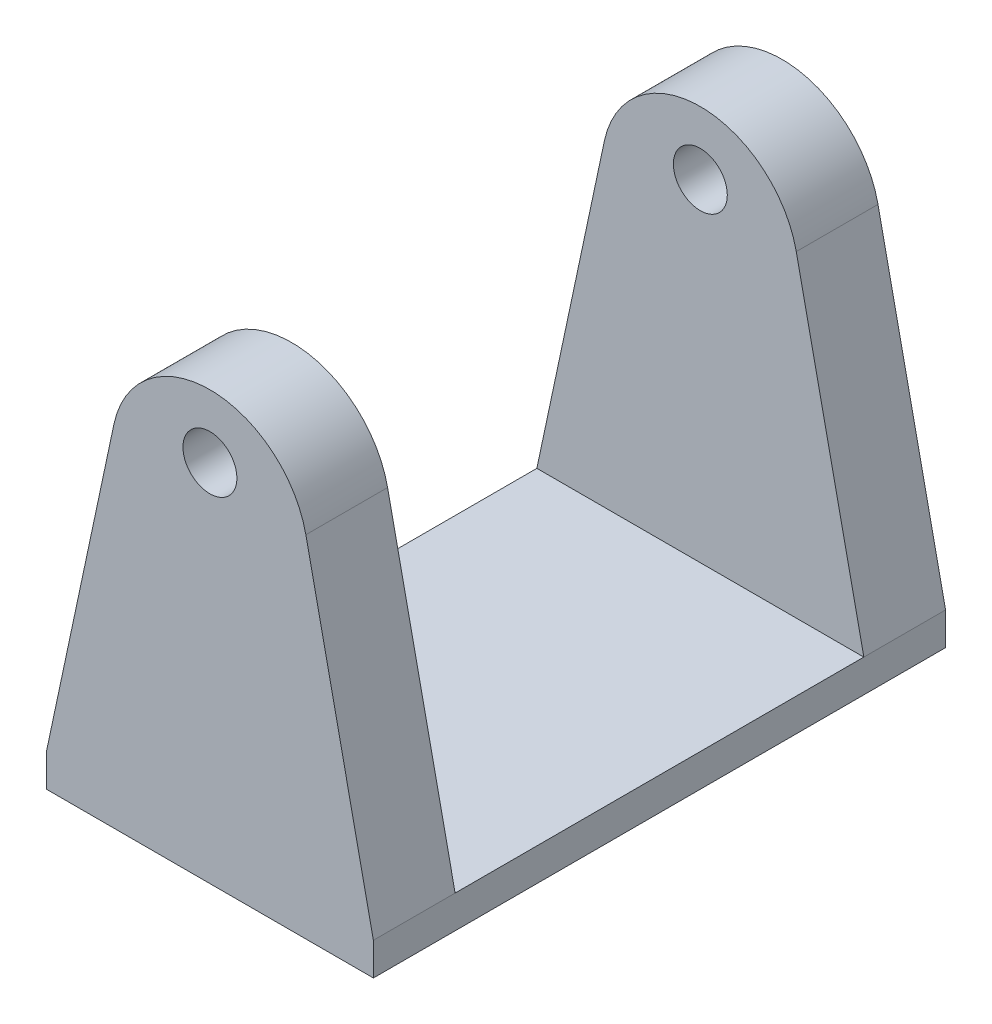
SolidWorks part; units mm, degrees
ref_plane "Front Plane" through (0, 0, 0) normal (0, 0, 1) x (1, 0, 0)
ref_plane "Top Plane" through (0, 0, 0) normal (0, 1, 0) x (1, 0, 0)
ref_plane "Right Plane" through (0, 0, 0) normal (1, 0, 0) x (0, 0, -1)
sketch "Sketch2" plane through (0, 0, 0) normal (0, 1, 0) x (1, 0, 0)
  line L1 (0, 0) -> (20, 0)
  line L2 (0, 0) -> (0, 35)
  line L3 (0, 35) -> (20, 35)
  line L4 (20, 0) -> (20, 35)
extrude "Boss-Extrude2" add sketch "Sketch2" along normal blind 2
sketch3d "3DSketch3"
  line L0 (10, 2, 0) -> (10, 49, 0)
  line L1 (0, 2, 0) -> (20, 2, 0) construction
  line L2 (10, 49, 0) -> (0, 2, 0)
  line L3 (0, 2, 0) -> (20, 2, 0)
  line L4 (20, 2, 0) -> (10, 49, 0)
  point P8 (0, 0, 0)
  point P9 (10, 25.828, 0)
  point P10 (10, 53.1292, 0)
  point P11 (10, 50.8187, 0)
extrude "Boss-Extrude5" add sketch "3DSketch3" along direction (0, 0, 1) on the side against the normal blind 5 contours L2 L3 L4
sketch3d "3DSketch4"
  line L0 (10, 2, -35) -> (10, 49, -35)
  line L1 (20, 2, -35) -> (0, 2, -35) construction
  line L2 (10, 49, -35) -> (0, 2, -35)
  line L3 (0, 2, -35) -> (20, 2, -35)
  line L4 (20, 2, -35) -> (10, 49, -35)
  point P8 (10, 45.7333, -35)
  point P9 (10, 50.8103, -35)
  point P10 (10, 48.7995, -35)
  point P11 (10, 37.9936, -35)
  point P12 (10, 56.0697, -35)
  point P13 (10, 51.4178, -35)
  point P14 (10, 45.4786, -35)
extrude "Boss-Extrude6" add sketch "3DSketch4" along direction (0, 0, 1) on the side of the normal blind 5 contours L2 L3 L4
fillet "Fillet1" radius 6 2 edges
sketch3d "3DSketch5"
  line L0 (10, 2, -5) -> (10, 22.3, -5)
  line L1 (0, 2, -5) -> (20, 2, -5) construction
  line L2 (10, 2, -30) -> (10, 22.3, -30)
  line L3 (0, 2, -30) -> (20, 2, -30) construction
  point P8 (0, 0, 0)
  point P9 (10, 15.4405, -5)
  point P10 (10, 13.0209, -5)
  point P11 (10, 13.0209, -5)
  point P12 (10, 22.5355, -5)
  point P13 (10, 12.0863, -30)
  point P14 (10, 20.5807, -30)
hole_wizard "Preforo da maschiare M4-1" positions "Sketch4" profile "Sketch5" hole size "M4" standard "GB"
sketch "Sketch4" plane through (0, 0, -30) normal (0, 0, 1) x (1, 0, 0)
  point P0 (10, 22.3)
sketch "Sketch5" plane through (10, 22.3, -30) normal (1, 0, 0) x (0, -1, 0)
  line L0 (0, 0) -> (0, 5.0001)
  line L1 (0, 5.0001) -> (1.65, 5.0001)
  line L2 (1.65, 5.0001) -> (1.65, 0)
  line L5 (1.65, 0) -> (0, 0)
  line L11 (0, -6.35) -> (0, 107.95) construction
  dimension "Thru Hole Dia." = 3.3
  dimension "Thru Hole Depth" = 5.0001
hole_wizard "Preforo da maschiare M4-2" positions "Sketch6" profile "Sketch7" hole size "M4" standard "GB" end condition through all
sketch "Sketch6" plane through (0, 0, -5) normal (0, 0, -1) x (-1, 0, 0)
  point P0 (-10, 22.3)
  point P3 (0, 0)
sketch "Sketch7" plane through (10, 22.3, -5) normal (1, 0, 0) x (0, 1, 0)
  line L0 (0, 0) -> (0, 5.0001)
  line L1 (0, 5.0001) -> (1.65, 5.0001)
  line L2 (1.65, 5.0001) -> (1.65, 0)
  line L5 (1.65, 0) -> (0, 0)
  line L11 (0, -6.35) -> (0, 107.95) construction
  dimension "Thru Hole Dia." = 3.3
  dimension "Thru Hole Depth" = 5.0001
